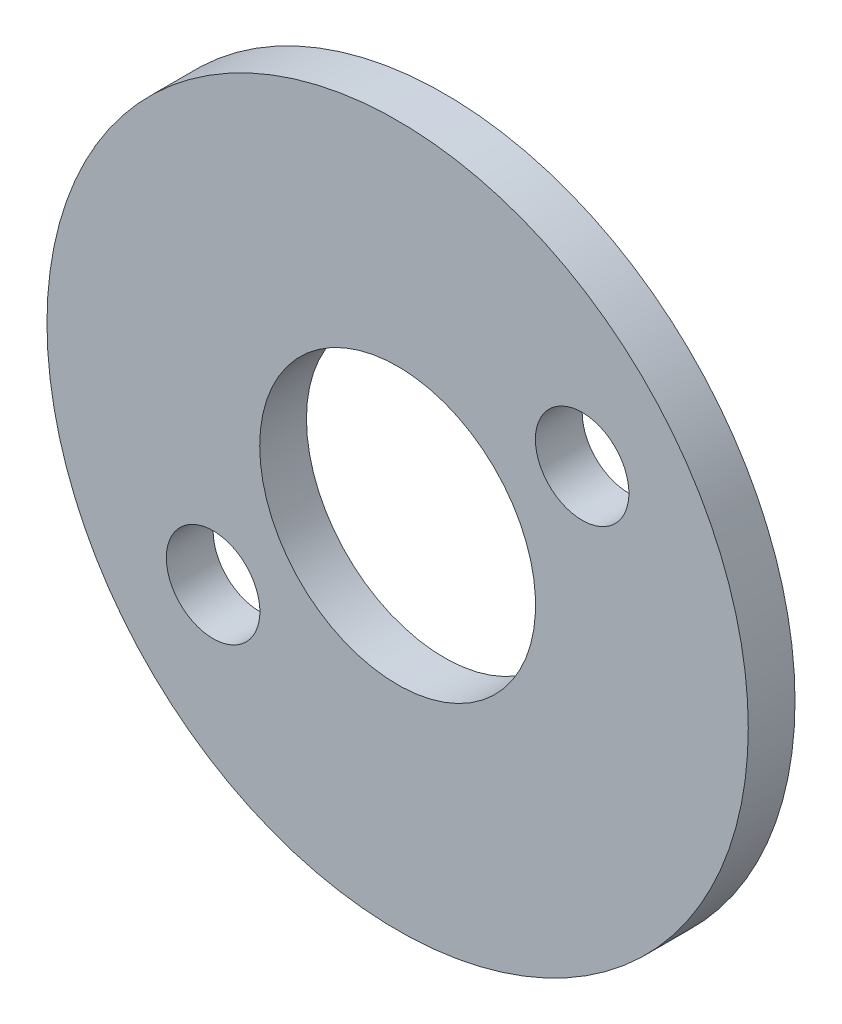
SolidWorks part; units mm, degrees
ref_plane "Face" through (0, 0, 0) normal (0, 0, 1) x (1, 0, 0)
ref_plane "Dessus" through (0, 0, 0) normal (0, 1, 0) x (1, 0, 0)
ref_plane "Droite" through (0, 0, 0) normal (1, 0, 0) x (0, 0, -1)
sketch "Esquisse1" plane through (0, 0, 0) normal (0, 0, 1) x (1, 0, 0)
  circle A0 centre (0, 0) radius 7.5
  dimension "D1" = 15
extrude "Boss.-Extru.1" add sketch "Esquisse1" along normal blind 1
sketch "Esquisse2" plane through (0, 0, 0) normal (0, 0, -1) x (-1, 0, 0)
  circle A0 centre (0, 0) radius 2.95
  circle A1 centre (-3.9468, 3.0697) radius 1
  circle A2 centre (3.9468, -3.0697) radius 1
  circle A3 centre (0, 0) radius 2.95 construction
  circle A4 centre (-3.9468, 3.0697) radius 1 construction
  circle A5 centre (3.9468, -3.0697) radius 1 construction
extrude "Enlèv. mat.-Extru.1" cut sketch "Esquisse2" against normal through all
